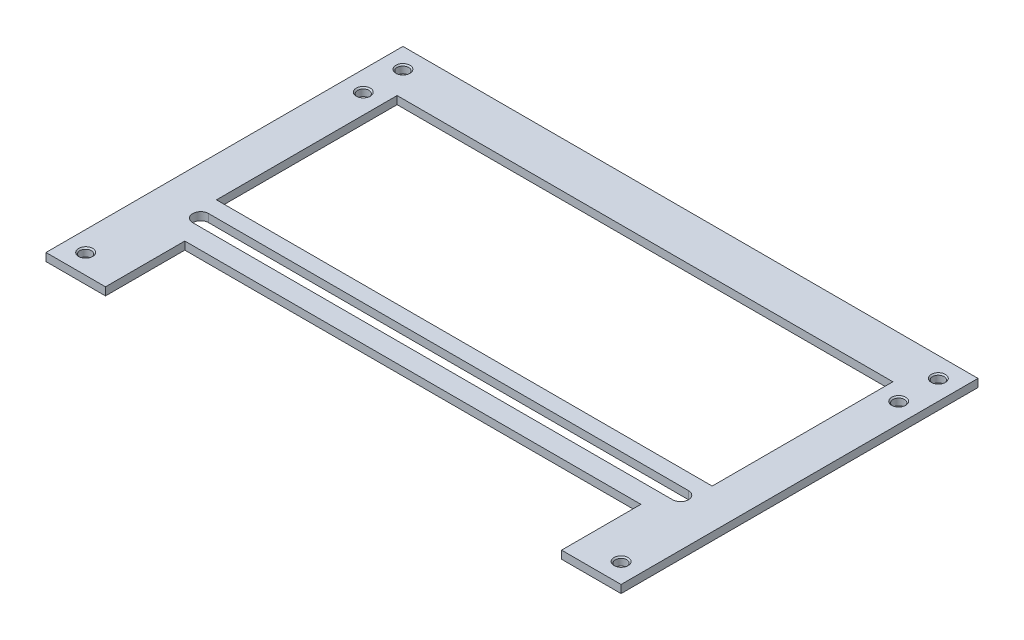
SolidWorks part; units mm, degrees
ref_plane "前视基准面" through (0, 0, 0) normal (0, 0, 1) x (1, 0, 0)
ref_plane "上视基准面" through (0, 0, 0) normal (0, 1, 0) x (1, 0, 0)
ref_plane "右视基准面" through (0, 0, 0) normal (1, 0, 0) x (0, 0, -1)
other "Configuration Table"
sketch "草图1" plane through (0, 0, 0) normal (0, 1, 0) x (1, 0, 0)
  line L0 (0, 0) -> (0, -10)
  line L2 (0, 0) -> (0, 80)
  line L3 (0, 80) -> (145, 80)
  line L4 (145, 0) -> (145, 80)
  line L5 (0, -10) -> (15, -10)
  line L6 (15, -10) -> (15, 0)
  line L7 (72.5, 80) -> (72.5, 0) construction
  line L8 (145, -10) -> (130, -10)
  line L9 (130, -10) -> (130, 0)
  line L10 (145, 0) -> (145, -10)
  line L11 (15, 0) -> (15, 10)
  line L12 (15, 10) -> (130, 10)
  line L13 (130, 10) -> (130, 0)
  dimension "D1" = 145
  dimension "D2" = 80
  dimension "D3" = 10
  dimension "D4" = 15
extrude "凸台-拉伸1" add sketch "草图1" along normal blind 2
sketch "草图2" plane through (0, 2, 0) normal (0, 1, 0) x (1, 0, 0)
  line L0 (0, 80) -> (5, 80) construction
  line L1 (145, 80) -> (0, 80) construction
  line L2 (5, 80) -> (5, 75) construction
  line L6 (0, 35) -> (145, 35) construction
  line L7 (0, 80) -> (0, -10) construction
  line L8 (145, -10) -> (145, 80) construction
  line L9 (5, -5) -> (5, 65) construction
  line L11 (145, 80) -> (0, 80) construction
  circle A2 centre (140, -5) radius 1.75
  circle A3 centre (5, -5) radius 1.75
  circle A4 centre (5, 65) radius 1.75
  circle A5 centre (140, 65) radius 1.75
  point P6 (5, 75)
  point P17 (140, 75)
  point P19 (140, -5)
  point P21 (5, -5)
  point P32 (5, 75)
  point P34 (5, 65)
  point P46 (140, 65)
  point P52 (5, 65)
  dimension "D3" = 15
  dimension "D1" = 5
  dimension "D2" = 5
hole_wizard "M3.5 螺纹孔2" positions "草图2" profile "草图5" tap size "M3.5" standard "GB" end condition through all
sketch "草图5" plane through (5, 2, -65) normal (1, 0, 0) x (0, 0, 1)
  line L0 (0, 0) -> (0, 2)
  line L1 (0, 2) -> (1.45, 2)
  line L2 (1.45, 2) -> (1.45, 0.325)
  line L3 (1.45, 0.325) -> (1.775, 0)
  line L5 (1.775, 0) -> (0, 0)
  line L6 (-1.45, 0.325) -> (-1.775, 0) construction
  line L11 (0, -6.35) -> (0, 107.95) construction
  dimension "通孔螺纹孔钻头直径" = 2.9
  dimension "通孔螺纹孔钻头深度" = 2
  dimension "近端锥形沉头孔直径" = 3.55
  dimension "近端锥形沉头孔角度" = 90
cosmetic thread "孔螺蚊线4" parameters "D2"=3.5
cosmetic thread "孔螺蚊线5" parameters "D2"=3.5
cosmetic thread "孔螺蚊线6" parameters "D2"=3.5
cosmetic thread "孔螺蚊线7" parameters "D2"=3.5
cosmetic thread "孔螺蚊线8" parameters "D2"=3.5
cosmetic thread "孔螺蚊线9" parameters "D2"=3.5
sketch "草图6" plane through (0, 2, 0) normal (0, 1, 0) x (1, 0, 0)
  line L0 (0, 0) -> (0, 17) construction
  line L1 (0, 80) -> (0, -10) construction
  line L2 (0, 17) -> (12, 17) construction
  line L3 (145, 17) -> (133, 17) construction
  line L4 (145, -10) -> (145, 80) construction
  line L5 (12, 17) -> (133, 17) construction
  line L6 (12, 19) -> (133, 19)
  line L7 (12, 15) -> (133, 15)
  arc A0 (12, 19) -> (12, 15) centre (12, 17) ccw
  arc A1 (133, 15) -> (133, 19) centre (133, 17) ccw
  point P10 (72.5, 17)
  point P15 (0, 0)
  dimension "D1" = 17
  dimension "D2" = 12
  dimension "D3" = 12
extrude "切除-拉伸1" cut sketch "草图6" against normal blind 3
sketch "草图7" plane through (0, 2, 0) normal (0, 1, 0) x (1, 0, 0)
  line L0 (10, 22.978) -> (10, 68.5298)
  line L1 (135, 22.978) -> (135, 68.5298)
  line L2 (135, 68.5298) -> (10, 68.5298)
  line L5 (10, 22.978) -> (135, 22.978)
extrude "切除-拉伸2" cut sketch "草图7" against normal blind 3
